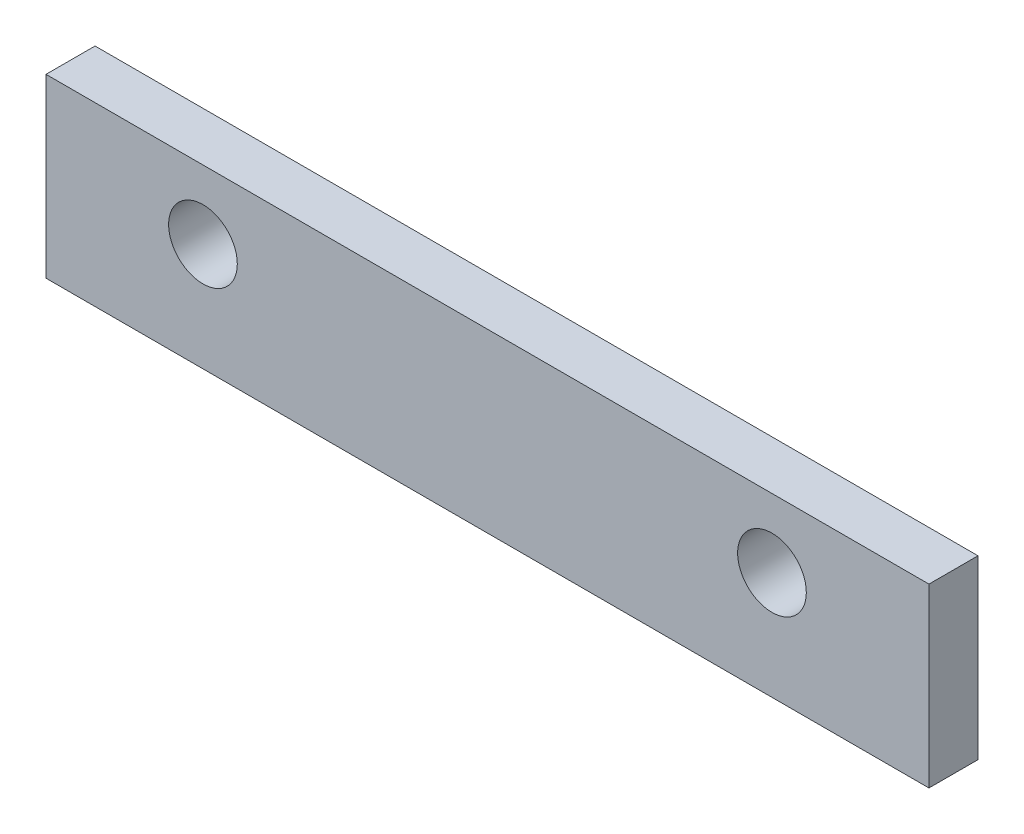
SolidWorks part; units mm, degrees
ref_plane "Front" through (0, 0, 0) normal (0, 0, 1) x (1, 0, 0)
ref_plane "Top" through (0, 0, 0) normal (0, 1, 0) x (1, 0, 0)
ref_plane "Right" through (0, 0, 0) normal (1, 0, 0) x (0, 0, -1)
sketch "Sketch1" plane through (0, 0, 0) normal (0, 0, 1) x (1, 0, 0)
  line L0 (-4.1747, 0) -> (4.6563, 0) construction
  line L1 (-22.5, 4.5) -> (22.5, 4.5)
  line L2 (-22.5, 4.5) -> (-22.5, -4.5)
  line L3 (-22.5, -4.5) -> (22.5, -4.5)
  line L4 (22.5, 4.5) -> (22.5, -4.5)
  line L5 (0, 2.6056) -> (0, -2.169) construction
  circle A0 centre (-14.5, 1) radius 1.75
  circle A1 centre (14.5, 1) radius 1.75
  dimension "D5" = 3.5
  dimension "D1" = 45
  dimension "D2" = 9
  dimension "D3" = 29
  dimension "D4" = 3.5
extrude "Boss-Extrude1" add sketch "Sketch1" along normal blind 2.5
